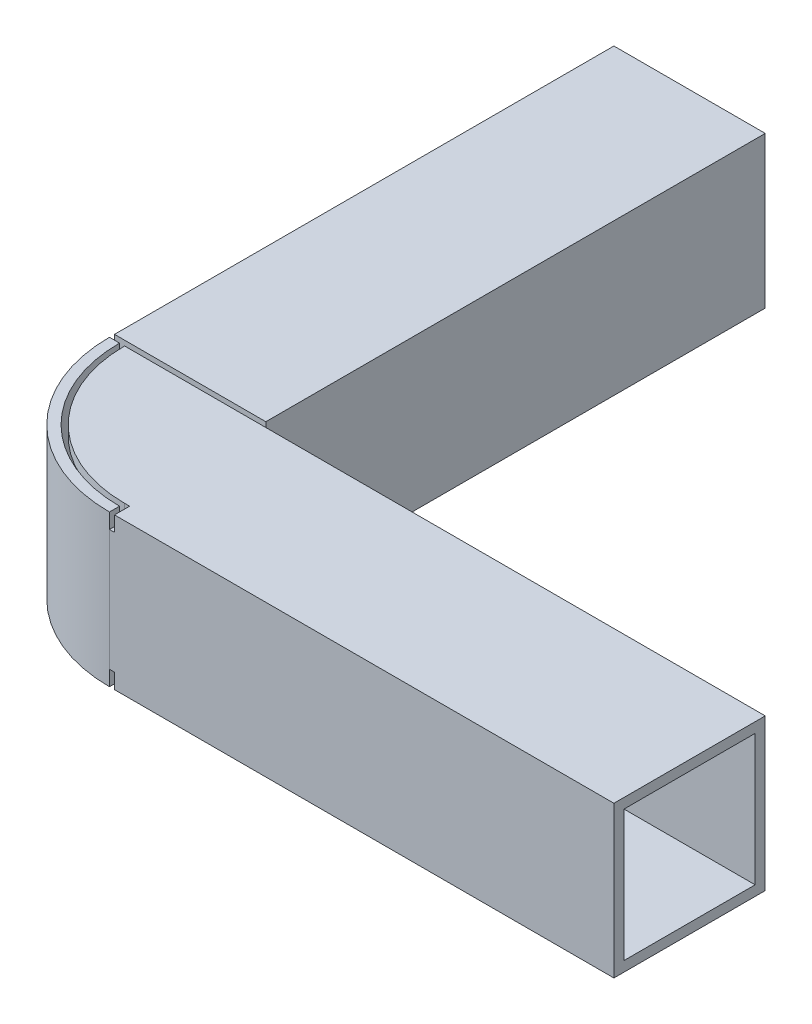
SolidWorks part; units mm, degrees
ref_plane "前视基准面" through (0, 0, 0) normal (0, 0, 1) x (1, 0, 0)
ref_plane "上视基准面" through (0, 0, 0) normal (0, 1, 0) x (1, 0, 0)
ref_plane "右视基准面" through (0, 0, 0) normal (1, 0, 0) x (0, 0, -1)
other "Configuration Table"
sketch "草图1" plane through (0, 0, 0) normal (0, 1, 0) x (1, 0, 0)
  line L0 (0, 0) -> (100, 0)
  line L1 (0, 0) -> (0, 100)
  dimension "D1" = 100
extrude "拉伸-薄壁1" add sketch "草图1" along normal mid plane 30 thin
fillet "圆角1" radius 30 1 edges at (-30, 0, 30)
shell "抽壳1" thickness 2
sketch "草图2" plane through (0, 15, 0) normal (0, 1, 0) x (1, 0, 0)
  line L3 (0, -28) -> (0, -27)
  line L4 (0, 0) -> (-27, 0)
  line L5 (0, 1) -> (-28, 1)
  line L6 (0, 0) -> (0, 100) construction
  line L7 (-28, 0) -> (-28, 100) construction
  line L8 (-28, 1) -> (-28, 0)
  arc A3 (-28, 0) -> (0, -28) centre (0, 0) ccw construction
  arc A4 (-28, 0) -> (0, -28) centre (0, 0) ccw
  arc A5 (-27, 0) -> (0, -27) centre (0, 0) ccw
  line M12 (0, 0) -> (0, 100)
  dimension "D2" = 1
  dimension "D1" = 1
extrude "切除-拉伸1" cut sketch "草图2" against normal through all and the other way through all contours A5 L4 L5 L8 A4 L3 M12
sketch "草图3" plane through (0, 15, 0) normal (0, 1, 0) x (1, 0, 0)
  line L0 (-28, 0) -> (-30, 0)
  line L1 (-30, 0) -> (-30, 1)
  line L2 (-30, 1) -> (-28, 1)
  line L3 (-28, 1) -> (-28, 0)
  line L4 (-30, 0) -> (-30, 100) construction
  line L5 (1, -27) -> (1, -30)
  line L6 (1, -30) -> (0, -30)
  line L7 (0, -30) -> (0, -27)
  line L8 (0, -27) -> (1, -27)
  line L9 (0, -28) -> (0, -27) construction
  arc A0 (-27, 0) -> (0, -27) centre (0, 0) ccw construction
  point P4 (0, -30)
  point P14 (0, -27)
  point P21 (0.807, -27.1353)
  dimension "D1" = 1
extrude "切除-拉伸2" cut sketch "草图3" against normal blind 3
mirror "镜向1" about plane through (0, 0, 0) normal (0, 1, 0) of "切除-拉伸2"
